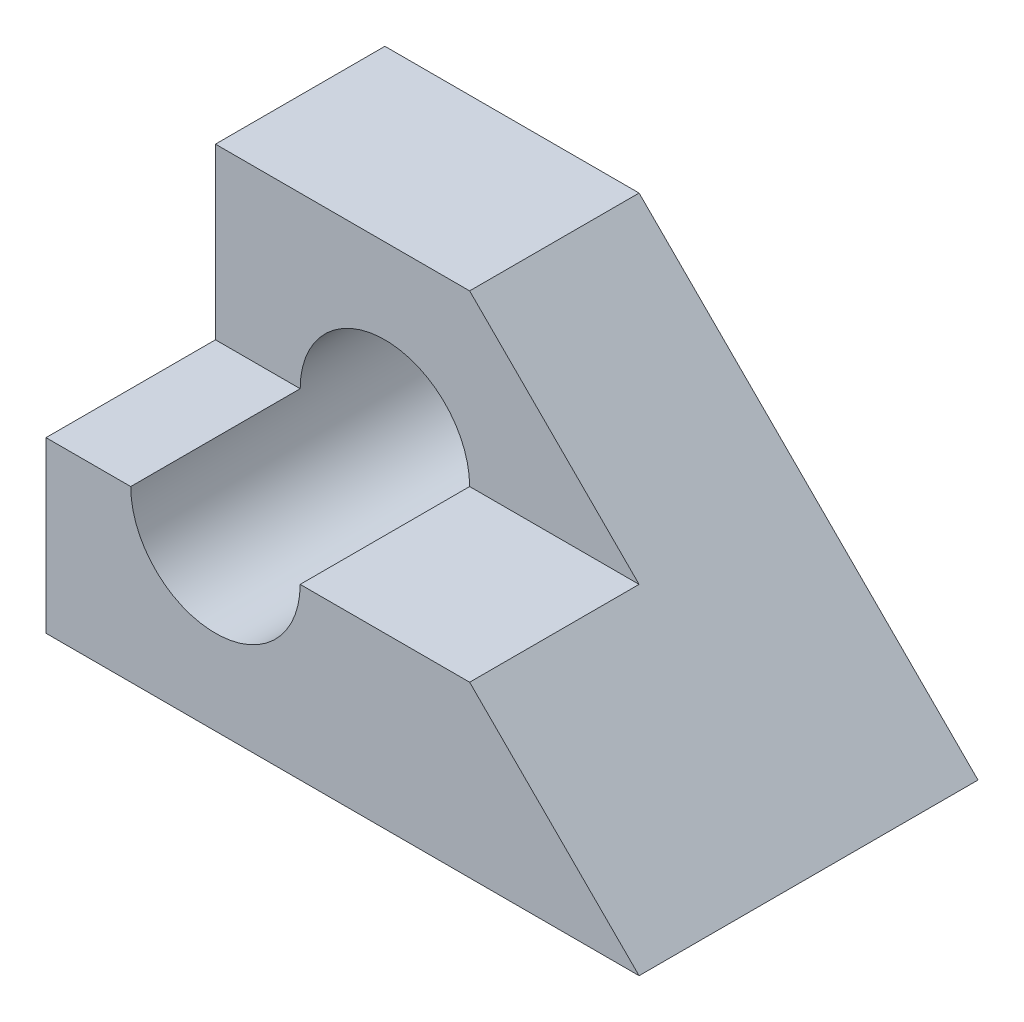
SolidWorks part; units mm, degrees
ref_plane "정면" through (0, 0, 0) normal (0, 0, 1) x (1, 0, 0)
ref_plane "윗면" through (0, 0, 0) normal (0, 1, 0) x (1, 0, 0)
ref_plane "우측면" through (0, 0, 0) normal (1, 0, 0) x (0, 0, -1)
sketch "스케치1" plane through (0, 0, 0) normal (1, 0, 0) x (0, 0, -1)
  line L1 (0, 0) -> (40, 0)
  line L2 (0, 0) -> (0, 20)
  line L3 (20, 40) -> (40, 40)
  line L4 (40, 0) -> (40, 40)
  line L7 (0, 20) -> (20, 20)
  line L8 (20, 40) -> (20, 20)
  dimension "D1" = 20
  dimension "D2" = 40
  dimension "D3" = 20
  dimension "D4" = 40
extrude "보스-돌출1" add sketch "스케치1" against normal blind 70
sketch "스케치2" plane through (0, 0, 0) normal (0, 0, 1) x (1, 0, 0)
sketch "스케치3" plane through (0, 0, -40) normal (0, 0, -1) x (-1, 0, 0)
  line L0 (0, 0) -> (40, 40)
  line L1 (70, 40) -> (0, 40) construction
  line L2 (40, 40) -> (0, 40)
  line L3 (0, 40) -> (0, 0)
  line L4 (70, 0) -> (0, 0) construction
  line L5 (70, 0) -> (70, 40) construction
  circle A0 centre (50, 20) radius 10
  dimension "D1" = 20
  dimension "D2" = 20
  dimension "D3" = 20
  dimension "D4" = 40
extrude "컷-돌출1" cut sketch "스케치3" against normal blind 70
